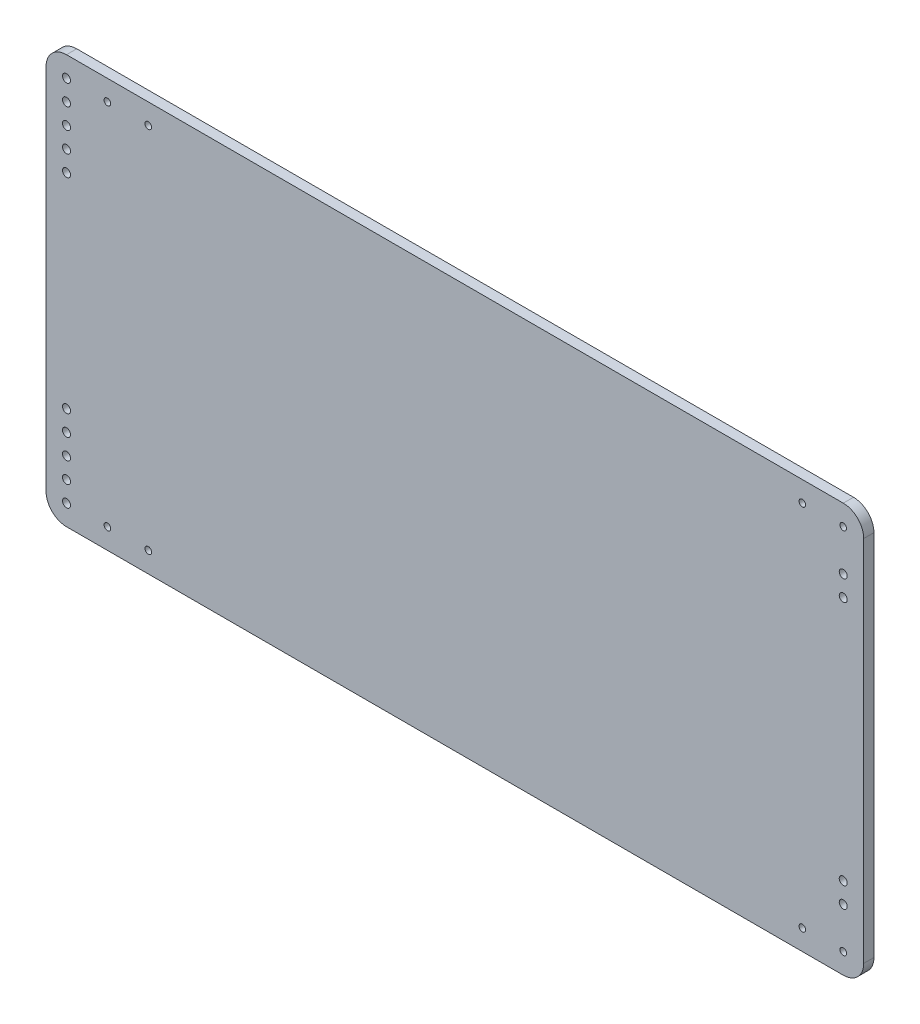
SolidWorks part; units mm, degrees
material "PC High Viscosity"
ref_plane "Front Plane" through (0, 0, 0) normal (0, 0, 1) x (1, 0, 0)
ref_plane "Top Plane" through (0, 0, 0) normal (0, 1, 0) x (1, 0, 0)
ref_plane "Right Plane" through (0, 0, 0) normal (1, 0, 0) x (0, 0, -1)
sketch "Sketch1" plane through (0, 0, 0) normal (0, 0, 1) x (1, 0, 0)
  line L1 (12.7, 0) -> (495.3, 0)
  line L2 (0, 12.7) -> (0, 241.3)
  line L3 (12.7, 254) -> (495.3, 254)
  line L4 (508, 12.7) -> (508, 241.3)
  arc A0 (495.3, 254) -> (508, 241.3) centre (495.3, 241.3) cw
  arc A1 (495.3, 0) -> (508, 12.7) centre (495.3, 12.7) ccw
  arc A2 (12.7, 0) -> (0, 12.7) centre (12.7, 12.7) cw
  arc A3 (0, 241.3) -> (12.7, 254) centre (12.7, 241.3) cw
  point P7 (508, 254)
  point P10 (508, 0)
  point P13 (0, 0)
  point P16 (0, 254)
  dimension "D3" = 12.7
  dimension "D1" = 508
  dimension "D2" = 254
extrude "Boss-Extrude1" add sketch "Sketch1" along normal blind 6.35
sketch "Sketch2" plane through (0, 0, 6.35) normal (0, 0, 1) x (1, 0, 0)
  line L10 (495.3, 254) -> (12.7, 254) construction
  line L11 (0, 241.3) -> (0, 12.7) construction
  line L12 (-20.2403, 127) -> (522.5431, 127) construction
  circle A6 centre (12.7, 190.5) radius 2.5
  circle A7 centre (12.7, 203.2) radius 2.5
  circle A8 centre (12.7, 215.9) radius 2.5
  circle A9 centre (12.7, 228.6) radius 2.5
  circle A10 centre (12.7, 241.3) radius 2.4892
  circle A11 centre (38.1, 241.3) radius 2.0701
  circle A12 centre (63.5, 241.3) radius 2.0701
  circle A13 centre (63.5, 12.7) radius 2.0701
  circle A14 centre (38.1, 12.7) radius 2.0701
  circle A15 centre (12.7, 63.5) radius 2.5
  circle A16 centre (12.7, 50.8) radius 2.5
  circle A17 centre (12.7, 38.1) radius 2.5
  circle A18 centre (12.7, 25.4) radius 2.5
  circle A19 centre (12.7, 12.7) radius 2.4892
  dimension "D2" = 12.7
  dimension "D3" = 5
  dimension "D4" = 4.1402
  dimension "D5" = 4.1402
  dimension "D6" = 4.9784
  dimension "D7" = 5
  dimension "D8" = 5
  dimension "D9" = 5
  dimension "D10" = 12.7
  dimension "D11" = 127
  dimension "D12" = 25.4
  dimension "D13" = 25.4
  dimension "D14" = 12.7
  dimension "D15" = 12.7
  dimension "D16" = 12.7
  dimension "D17" = 12.7
extrude "Cut-Extrude1" cut sketch "Sketch2" against normal through all
sketch "Sketch3" plane through (0, 0, 6.35) normal (0, 0, 1) x (1, 0, 0)
  line L8 (495.3, 254) -> (12.7, 254) construction
  line L11 (508, 12.7) -> (508, 241.3) construction
  line L12 (-50.4543, 127) -> (582.5907, 127) construction
  circle A0 centre (469.8795, 241.3) radius 2.0701
  circle A1 centre (495.2795, 241.3) radius 2.0701
  circle A4 centre (495.2795, 215.9) radius 2.4892
  circle A5 centre (495.2795, 203.2) radius 2.4892
  circle A16 centre (469.8795, 12.7) radius 2.0701
  circle A17 centre (495.2795, 12.7) radius 2.0701
  circle A18 centre (495.2795, 38.1) radius 2.4892
  circle A19 centre (495.2795, 50.8) radius 2.4892
  dimension "D1" = 4.1402
  dimension "D2" = 4.9784
  dimension "D3" = 12.7
  dimension "D4" = 12.7205
  dimension "D5" = 127
  dimension "D10" = 25.4
  dimension "D13" = 25.4
  dimension "D15" = 12.7
extrude "Cut-Extrude2" cut sketch "Sketch3" against normal through all
